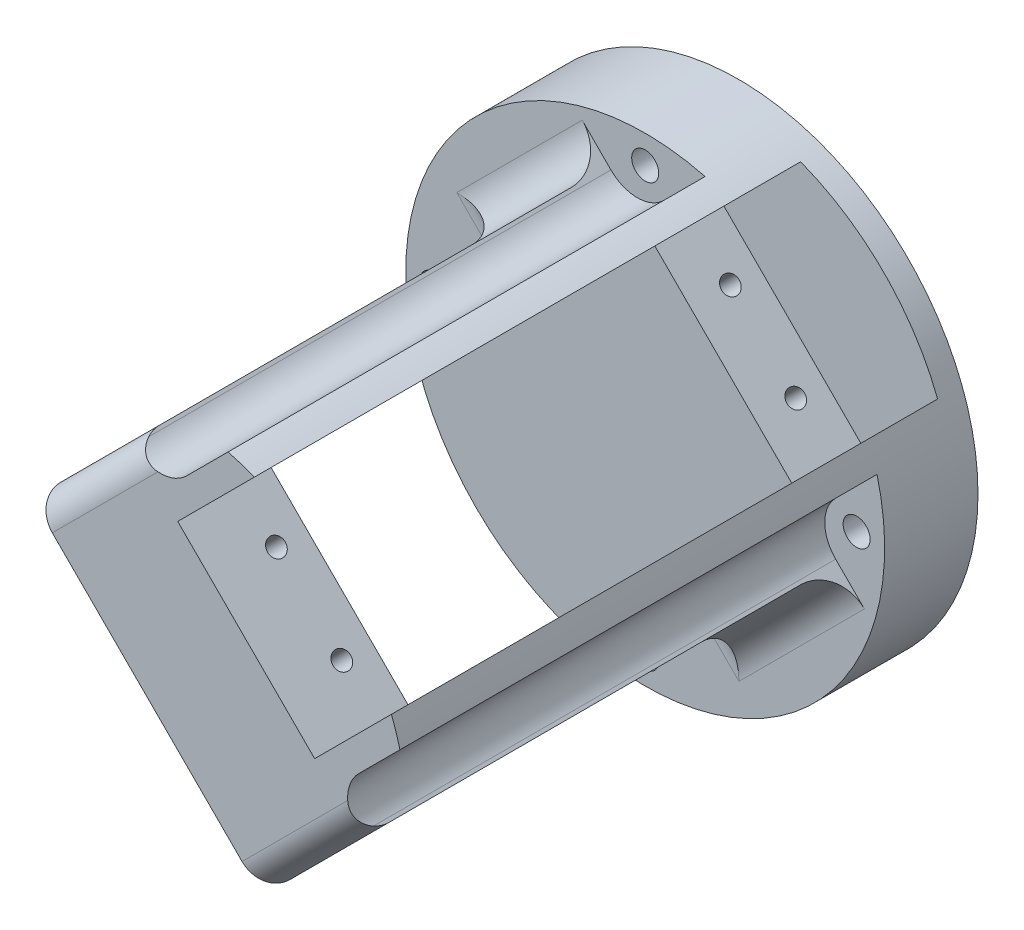
SolidWorks part; units mm, degrees
ref_plane "Front Plane" through (0, 0, 0) normal (0, 0, 1) x (1, 0, 0)
ref_plane "Top Plane" through (0, 0, 0) normal (0, 1, 0) x (1, 0, 0)
ref_plane "Right Plane" through (0, 0, 0) normal (1, 0, 0) x (0, 0, -1)
sketch "Sketch1" plane through (0, 0, 0) normal (0, 0, 1) x (1, 0, 0)
  circle A0 centre (0, 0) radius 25.65
  circle A2 centre (0, -22.65) radius 1.45
  circle A3 centre (0, -22.65) radius 1.45
  circle A4 centre (22.65, 0) radius 1.45
  circle A5 centre (22.65, 0) radius 1.45
  circle A6 centre (0, 22.65) radius 1.45
  circle A7 centre (0, 22.65) radius 1.45
  circle A8 centre (-22.65, 0) radius 1.45
  circle A9 centre (-22.65, 0) radius 1.45
  dimension "D1" = 0
  dimension "D2" = 0
  dimension "D3" = 0
  dimension "D4" = 0
extrude "Boss-Extrude1" add sketch "Sketch1" along normal blind 10 contours A0
sketch "Sketch2" plane through (0, 0, 10) normal (0, 0, 1) x (1, 0, 0)
  line L0 (0, 0) -> (18.1373, 18.1373) construction
  line L1 (1.0288, 15.7013) -> (15.7013, 1.0288)
  line L2 (15.7013, 1.0288) -> (19.2002, 4.5278) construction
  line L8 (10.6985, 10.6985) -> (11.2642, 10.1328) construction
  line L9 (10.1328, 11.2642) -> (11.2642, 10.1328) construction
  line L13 (1.0288, 15.7013) -> (9.2511, 23.9236)
  line L14 (15.7013, 1.0288) -> (23.9236, 9.2511)
  circle A0 centre (0, 0) radius 25.65 construction
  point P5 (10.6985, 10.6985)
  point P6 (8.3651, 8.3651)
  point P13 (10.6985, 10.6985)
  point P14 (8.3651, 8.3651)
  point P19 (12.3249, 12.3249)
  dimension "D1" = 10.52
  dimension "D2" = 3.3
  dimension "D3" = 20.75
extrude "Cut-Extrude2" cut sketch "Sketch2" against normal blind 7.4 and the other way through all
sketch "Sketch3" plane through (8.3651, 8.3651, 0) normal (0.7071, 0.7071, 0) x (0, 0, -1)
  line L0 (-10, 0) -> (-2.6, 0) construction
  line L1 (-10, 10.375) -> (-10, -10.375) construction
  line L2 (-2.6, 10.375) -> (-2.6, -10.375) construction
  circle A0 centre (-5.74, 4.95) radius 2.25 construction
  circle A1 centre (-5.74, 4.95) radius 0.95
  circle A2 centre (-5.74, -4.95) radius 0.95
  dimension "D1" = 2.7
  dimension "D2" = 4.5
  dimension "D3" = 2.01
  dimension "D4" = 1.9
extrude "Cut-Extrude3" cut sketch "Sketch3" against normal blind 15
sketch "Sketch4" plane through (0, 0, 10) normal (0, 0, 1) x (1, 0, 0)
  line L0 (1.0288, 15.7013) -> (15.7013, 1.0288) construction
  line L1 (9.2511, 23.9236) -> (1.0288, 15.7013) construction
  line L2 (-3.9209, 20.6511) -> (1.0288, 15.7013)
  line L3 (-3.9209, 20.6511) -> (-14.5275, 10.0445)
  line L4 (1.0288, 15.7013) -> (-9.5778, 5.0947)
  line L5 (-14.5275, 10.0445) -> (-9.5778, 5.0947)
  line L6 (0, 0) -> (12.9711, 12.9711) construction
  line L7 (15.7013, 1.0288) -> (5.0947, -9.5778)
  line L8 (10.0445, -14.5275) -> (5.0947, -9.5778)
  line L9 (20.6511, -3.9209) -> (10.0445, -14.5275)
  line L10 (20.6511, -3.9209) -> (15.7013, 1.0288)
  dimension "D1" = 15
  dimension "D2" = 7
extrude "Boss-Extrude2" add sketch "Sketch4" along normal blind 41.11
sketch "Sketch5" plane through (0, 0, 51.11) normal (0, 0, 1) x (1, 0, 0)
  line L0 (-3.9209, 20.6511) -> (-14.5275, 10.0445)
  line L1 (-3.9209, 20.6511) -> (20.6511, -3.9209)
  line L2 (-14.5275, 10.0445) -> (10.0445, -14.5275)
  line L3 (20.6511, -3.9209) -> (10.0445, -14.5275)
  point P0 (20.6511, -3.9209)
extrude "Boss-Extrude3" add sketch "Sketch5" along normal blind 10
sketch "Sketch6" plane through (8.3651, 8.3651, 0) normal (0.7071, 0.7071, 0) x (0, 0, -1)
  line L0 (-51.11, 10.375) -> (-10, 10.375) construction
  line L1 (-30.055, 10.375) -> (-30.055, -10.375) construction
  line L2 (-51.11, -10.375) -> (-10, -10.375) construction
  circle A0 centre (-5.74, -4.95) radius 0.95 construction
  circle A1 centre (-5.74, 4.95) radius 0.95 construction
  circle A2 centre (-5.74, -4.95) radius 0.95
  circle A3 centre (-5.74, 4.95) radius 0.95
  circle A4 centre (-54.37, -4.95) radius 0.95
  circle A5 centre (-54.37, 4.95) radius 0.95
  point P0 (-30.055, 10.375)
  dimension "D1" = 20.055
extrude "Cut-Extrude4" cut sketch "Sketch6" against normal blind 15
fillet "Fillet1" radius 4 4 edges at (-9.2242, 15.3478, 10) (-12.0526, 7.5696, 10) (15.3478, -9.2242, 10) (7.5696, -12.0526, 10)
sketch "Sketch7" plane through (0, 0, 10) normal (0, 0, 1) x (1, 0, 0)
  line L0 (-0.8446, 17.5747) -> (6.4155, 24.8347)
  line L1 (1.0288, 15.7013) -> (-6.7493, 23.4795) construction
  line L2 (-0.8446, 17.5747) -> (1.0288, 15.7013)
  line L3 (1.0288, 15.7013) -> (9.2511, 23.9236)
  line L4 (0, 0) -> (8.3651, 8.3651) construction
  line L6 (15.7013, 1.0288) -> (23.9236, 9.2511)
  line L7 (17.5747, -0.8446) -> (15.7013, 1.0288)
  line L8 (17.5747, -0.8446) -> (24.8347, 6.4155)
  arc A0 (9.2511, 23.9236) -> (23.9236, 9.2511) centre (0, 0) ccw construction
  line M6 (-6.7493, 23.4795) -> (1.0288, 15.7013)
  line M7 (1.0288, 15.7013) -> (9.2511, 23.9236)
  arc M8 (9.2511, 23.9236) -> (23.9236, 9.2511) centre (0, 0) ccw
  line M9 (23.9236, 9.2511) -> (15.7013, 1.0288)
  line M10 (15.7013, 1.0288) -> (23.4795, -6.7493)
extrude "Boss-Extrude4" add sketch "Sketch7" along normal up to surface (51.11 mm away) contours L0 M6 M7 M8 | L8 M10 M8 M9 up to face at (3.0618, 3.0618, 61.11)
fillet "Fillet2" radius 4 2 edges at (-0.8446, 17.5747, 35.555) (17.5747, -0.8446, 35.555)
fillet "Fillet3" radius 3 2 edges at (-9.2242, 15.3478, 61.11) (15.3478, -9.2242, 61.11)
